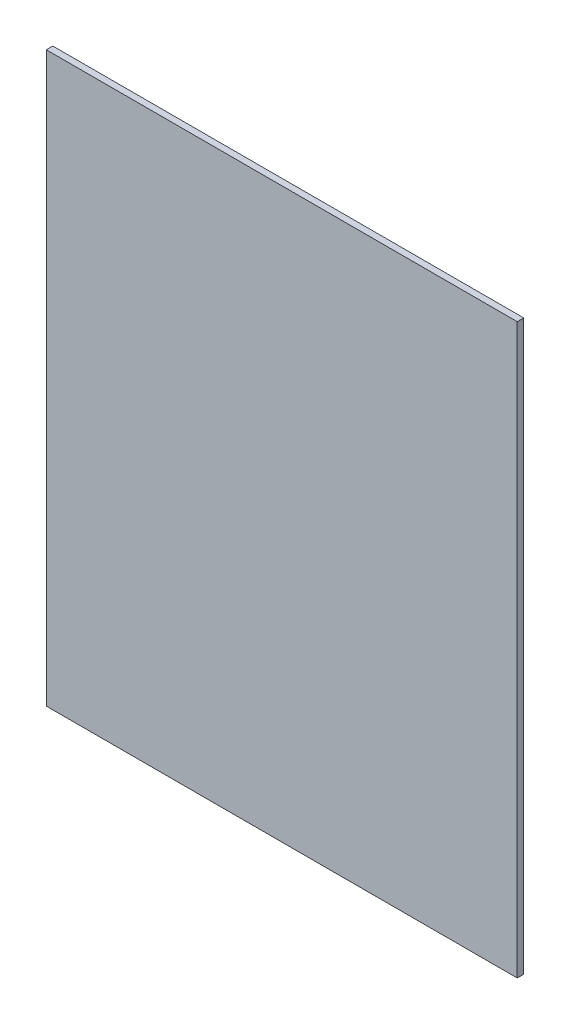
SolidWorks part; units mm, degrees
ref_plane "前视基准面" through (0, 0, 0) normal (0, 0, 1) x (1, 0, 0)
ref_plane "上视基准面" through (0, 0, 0) normal (0, 1, 0) x (1, 0, 0)
ref_plane "右视基准面" through (0, 0, 0) normal (1, 0, 0) x (0, 0, -1)
sketch "草图1" plane through (0, 0, 0) normal (0, 0, 1) x (1, 0, 0)
  line L1 (-7.25, 8.75) -> (7.25, 8.75)
  line L2 (-7.25, 8.75) -> (-7.25, -8.75)
  line L3 (-7.25, -8.75) -> (7.25, -8.75)
  line L4 (7.25, 8.75) -> (7.25, -8.75)
  line L5 (-7.25, 8.75) -> (7.25, -8.75) construction
  line L6 (-7.25, -8.75) -> (7.25, 8.75) construction
  point P0 (0, 0)
  dimension "D1" = 14.5
  dimension "D2" = 17.5
extrude "凸台-拉伸1" add sketch "草图1" along normal blind 0.2
